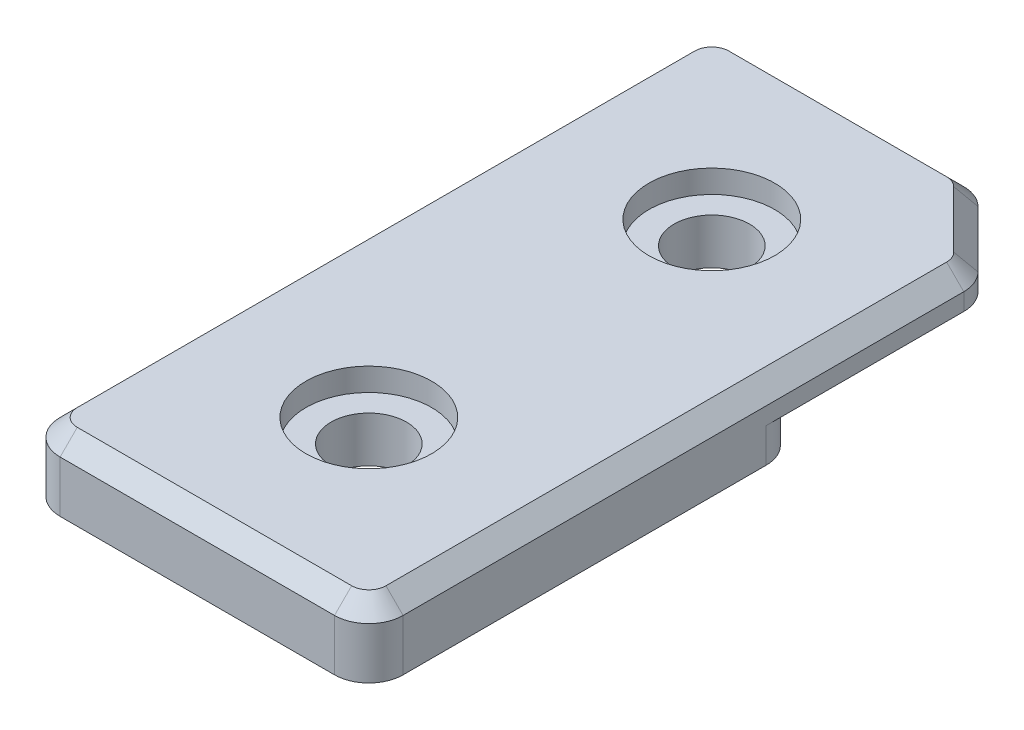
SolidWorks part; units mm, degrees
ref_plane "Frente" through (0, 0, 0) normal (0, 0, 1) x (1, 0, 0)
ref_plane "Topo" through (0, 0, 0) normal (0, 1, 0) x (1, 0, 0)
ref_plane "Lateral" through (0, 0, 0) normal (1, 0, 0) x (0, 0, -1)
sketch "Sketch1" plane through (0, 0, 0) normal (0, 1, 0) x (1, 0, 0)
  line L1 (-15, 30) -> (15, 30)
  line L2 (-15, 30) -> (-15, -30)
  line L3 (-15, -30) -> (15, -30)
  line L4 (15, 30) -> (15, -30)
  line L5 (-15, 30) -> (15, -30) construction
  line L6 (-15, -30) -> (15, 30) construction
  point P0 (0, 0)
  dimension "D1" = 30
  dimension "D2" = 60
extrude "Boss-Extrude1" add sketch "Sketch1" along normal blind 6
sketch "Sketch2" plane through (0, 0, 0) normal (0, -1, 0) x (1, 0, 0)
  line L0 (15, -6) -> (-9, -30)
  line L1 (15, 30) -> (15, -30) construction
  line L2 (15, -30) -> (-15, -30) construction
  line L3 (-9, -30) -> (15, -30)
  line L4 (15, -30) -> (15, -6)
  dimension "D1" = 24
extrude "Cut-Extrude1" cut sketch "Sketch2" against normal blind 3
sketch "Sketch3" plane through (0, 3, 0) normal (0, -1, 0) x (1, 0, 0)
  line L0 (15, -23.2825) -> (15, -30)
  line L2 (15, -30) -> (8.2825, -30)
  line L3 (-9, -30) -> (15, -30) construction
  line L4 (8.2825, -30) -> (15, -23.2825)
  line L8 (15, -6) -> (-9, -30) construction
  dimension "D1" = 9.5
extrude "Cut-Extrude2" cut sketch "Sketch3" against normal through all
fillet "Fillet1" radius 3 7 edges at (-15, 3, 30) (-15, 3, -30) (8.2825, 4.5, -30) (15, 4.5, -23.2825) (15, 3, 30) (15, 1.5, -6) (-9, 1.5, -30)
chamfer "Chamfer1" distance 1.5 angle 45 10 edges at (-14.1213, 6, -29.1213) (-2.4801, 6, -30) (8.1879, 6, -29.7716) (11.6412, 6, -26.6412) (14.7716, 6, -23.1879) (15, 6, 2.4801) (14.1213, 6, 29.1213) (0, 6, 30) (-14.1213, 6, 29.1213) (-15, 6, 0)
hole_wizard "CBORE for M6 Hex Socket Head Cap Screw1" positions "Sketch4" profile "Sketch5" counterbore size "M6" standard "DIN" end condition through all
sketch "Sketch4" plane through (0, 6, 0) normal (0, 1, 0) x (1, 0, 0)
  line L0 (0, 15) -> (0, -15) construction
  point P0 (0, -15)
  point P4 (0, 15)
  dimension "D1" = 30
sketch "Sketch5" plane through (0, 6, 15) normal (1, 0, 0) x (0, 0, 1)
  line L0 (0, 0) -> (0, 6)
  line L1 (0, 6) -> (3.3, 6)
  line L3 (3.3, 6) -> (3.3, 2)
  line L4 (3.3, 2) -> (5.5, 2)
  line L5 (5.5, 2) -> (5.5, 0)
  line L7 (5.5, 0) -> (0, 0)
  line L11 (0, -6.35) -> (0, 107.95) construction
  dimension "Thru Hole Dia." = 6.6
  dimension "Thru Hole Depth" = 6
  dimension "C'Bore Dia." = 11
  dimension "C'Bore Depth" = 2
